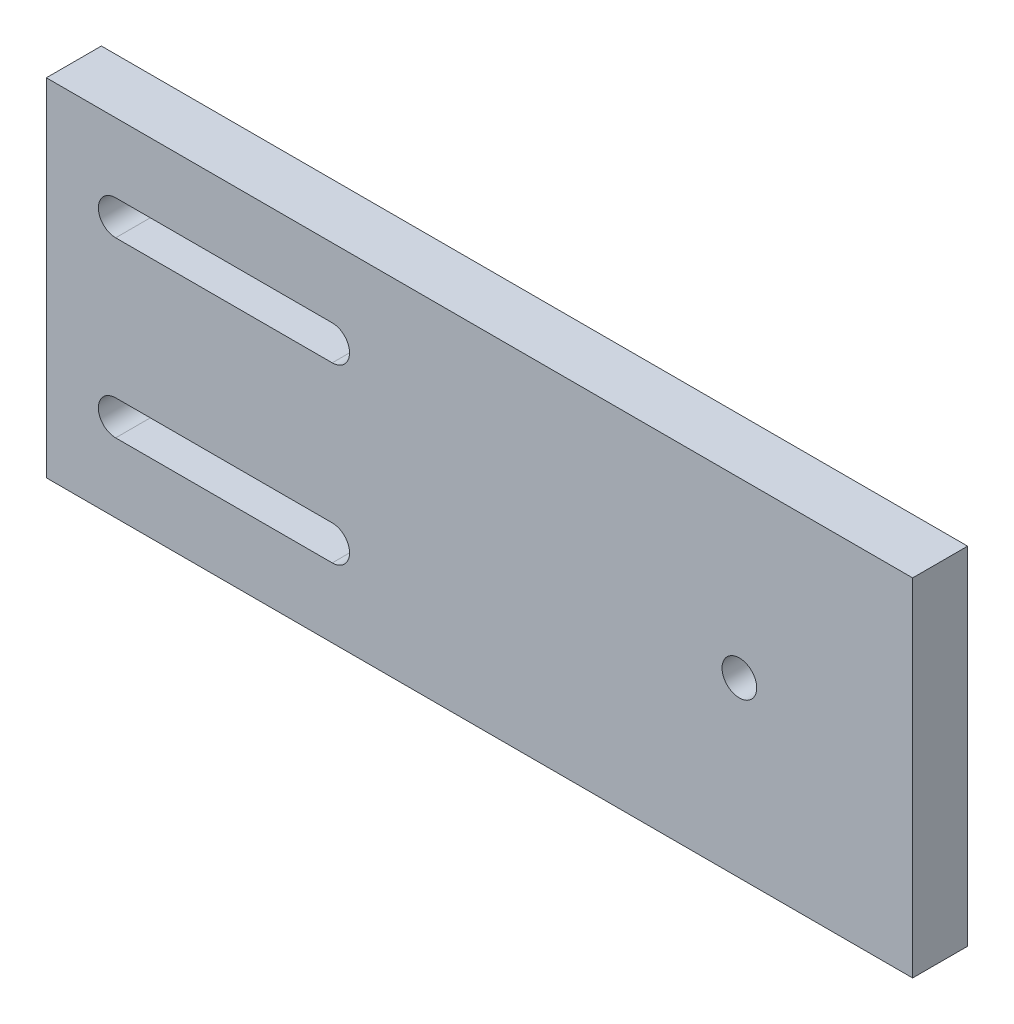
SolidWorks part; units mm, degrees
ref_plane "Front Plane" through (0, 0, 0) normal (0, 0, 1) x (1, 0, 0)
ref_plane "Top Plane" through (0, 0, 0) normal (0, 1, 0) x (1, 0, 0)
ref_plane "Right Plane" through (0, 0, 0) normal (1, 0, 0) x (0, 0, -1)
sketch "Sketch1" plane through (0, 0, 0) normal (0, 0, 1) x (1, 0, 0)
  line L0 (8, 32) -> (33, 32)
  line L1 (0, 0) -> (100, 0)
  line L2 (0, 0) -> (0, 40)
  line L3 (0, 40) -> (100, 40)
  line L4 (100, 0) -> (100, 40)
  line L5 (8, 28) -> (33, 28)
  line L6 (8, 12) -> (33, 12)
  line L7 (8, 8) -> (33, 8)
  circle A4 centre (80, 20) radius 2
  arc A5 (33, 32) -> (33, 28) centre (33, 30) cw
  arc A6 (8, 32) -> (8, 28) centre (8, 30) ccw
  arc A7 (33, 12) -> (33, 8) centre (33, 10) cw
  arc A8 (8, 12) -> (8, 8) centre (8, 10) ccw
  point P13 (100, 20)
  dimension "D11" = 4
  dimension "D3" = 40
  dimension "D12" = 20
  dimension "D8" = 4
  dimension "D9" = 10
  dimension "D10" = 8
  dimension "D13" = 25
  dimension "D7" = 100
  dimension "D14" = 25
  dimension "D15" = 4
  dimension "D16" = 10
extrude "Boss-Extrude1" add sketch "Sketch1" along normal blind 6.35
equation "\"D14@Sketch1\"=\"D13@Sketch1\""
equation "\"D15@Sketch1\"=\"D8@Sketch1\""
equation "\"D16@Sketch1\"=\"D9@Sketch1\""
